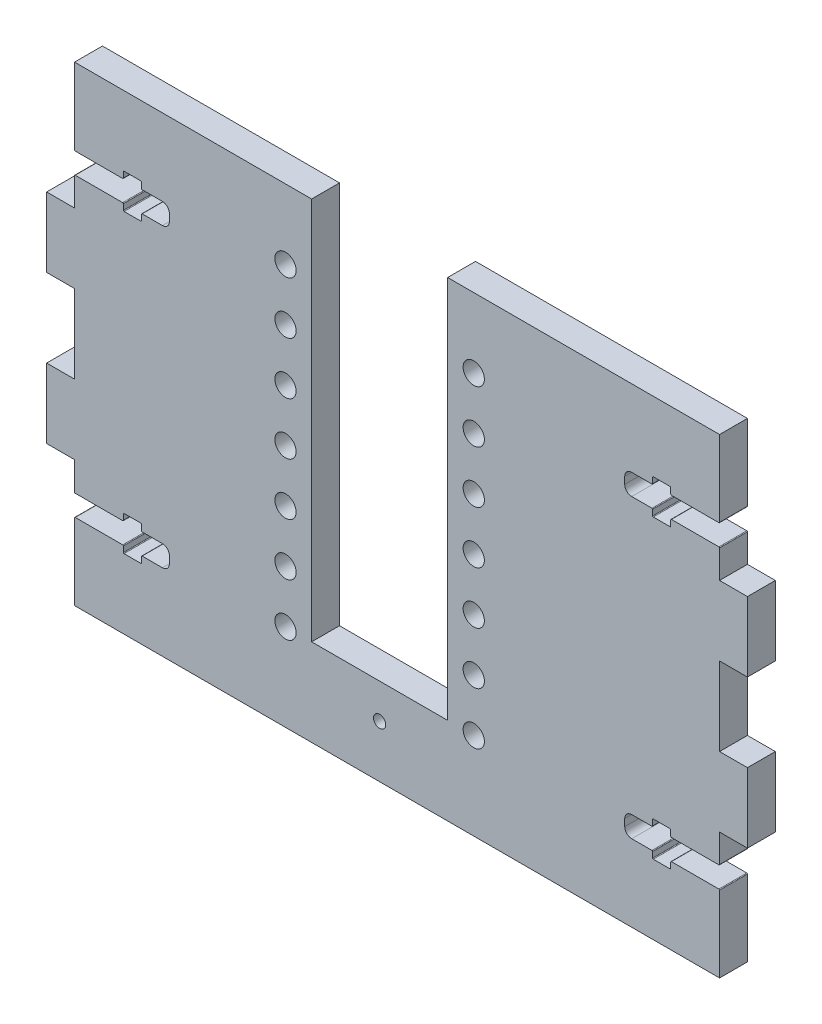
SolidWorks part; units mm, degrees
ref_plane "Front Plane" through (0, 0, 0) normal (0, 0, 1) x (1, 0, 0)
ref_plane "Top Plane" through (0, 0, 0) normal (0, 1, 0) x (1, 0, 0)
ref_plane "Right Plane" through (0, 0, 0) normal (1, 0, 0) x (0, 0, -1)
sketch "Model" plane through (0, 0, 0) normal (0, 0, 1) x (1, 0, 0)
  line L0 (-92.5, 21.8) -> (-92.5, 2)
  line L1 (-78.7, 22) -> (-92.3, 22)
  line L2 (-78.5, 20.2) -> (-78.5, 21.8)
  line L3 (-73.5, 20) -> (-78.3, 20)
  line L4 (-73.3, 21.8) -> (-73.3, 20.2)
  line L5 (-67.3, 22) -> (-73.1, 22)
  line L6 (-65.3, 26) -> (-65.3, 24)
  line L7 (-73.1, 28) -> (-67.3, 28)
  line L8 (-73.3, 29.8) -> (-73.3, 28.2)
  line L9 (-78.3, 30) -> (-73.5, 30)
  line L10 (-78.5, 28.2) -> (-78.5, 29.8)
  line L11 (-92.3, 28) -> (-78.7, 28)
  line L12 (-92.5, 36.25) -> (-92.5, 28.2)
  line L13 (-100.5, 36.25) -> (-92.5, 36.25)
  line L14 (-100.5, 56.25) -> (-100.5, 36.25)
  line L15 (-92.5, 56.25) -> (-100.5, 56.25)
  line L16 (-92.5, 78.75) -> (-92.5, 56.25)
  line L17 (-100.5, 78.75) -> (-92.5, 78.75)
  line L18 (-100.5, 98.75) -> (-100.5, 78.75)
  line L19 (-92.5, 98.75) -> (-100.5, 98.75)
  line L20 (-92.5, 106.8) -> (-92.5, 98.75)
  line L21 (-78.7, 107) -> (-92.3, 107)
  line L22 (-78.5, 105.2) -> (-78.5, 106.8)
  line L23 (-73.5, 105) -> (-78.3, 105)
  line L24 (-73.3, 106.8) -> (-73.3, 105.2)
  line L25 (-67.3, 107) -> (-73.1, 107)
  line L26 (-65.3, 111) -> (-65.3, 109)
  line L27 (-73.1, 113) -> (-67.3, 113)
  line L28 (-73.3, 114.8) -> (-73.3, 113.2)
  line L29 (-78.3, 115) -> (-73.5, 115)
  line L30 (-78.5, 113.2) -> (-78.5, 114.8)
  line L31 (-92.3, 113) -> (-78.7, 113)
  line L32 (-92.5, 133) -> (-92.5, 113.2)
  line L33 (-24.5, 135) -> (-90.5, 135)
  line L34 (-90.5, 135) -> (-92.5, 135)
  line L35 (-92.5, 133) -> (-92.5, 135)
  line L36 (-92.5, 2) -> (-92.5, 0)
  line L37 (90.5, 135) -> (14.5, 135)
  line L38 (92.5, 113.2) -> (92.5, 133)
  line L39 (78.7, 113) -> (92.3, 113)
  line L40 (78.5, 114.8) -> (78.5, 113.2)
  line L41 (73.5, 115) -> (78.3, 115)
  line L42 (73.3, 113.2) -> (73.3, 114.8)
  line L43 (67.3, 113) -> (73.1, 113)
  line L44 (65.3, 109) -> (65.3, 111)
  line L45 (73.1, 107) -> (67.3, 107)
  line L46 (73.3, 105.2) -> (73.3, 106.8)
  line L47 (78.3, 105) -> (73.5, 105)
  line L48 (78.5, 106.8) -> (78.5, 105.2)
  line L49 (92.3, 107) -> (78.7, 107)
  line L50 (92.5, 98.75) -> (92.5, 106.8)
  line L51 (100.5, 98.75) -> (92.5, 98.75)
  line L52 (100.5, 78.75) -> (100.5, 98.75)
  line L53 (92.5, 78.75) -> (100.5, 78.75)
  line L54 (92.5, 56.25) -> (92.5, 78.75)
  line L55 (100.5, 56.25) -> (92.5, 56.25)
  line L56 (100.5, 36.25) -> (100.5, 56.25)
  line L57 (92.5, 36.25) -> (100.5, 36.25)
  line L58 (92.5, 28.2) -> (92.5, 36.25)
  line L59 (78.7, 28) -> (92.3, 28)
  line L60 (78.5, 29.8) -> (78.5, 28.2)
  line L61 (73.5, 30) -> (78.3, 30)
  line L62 (73.3, 28.2) -> (73.3, 29.8)
  line L63 (67.3, 28) -> (73.1, 28)
  line L64 (65.3, 24) -> (65.3, 26)
  line L65 (73.1, 22) -> (67.3, 22)
  line L66 (73.3, 20.2) -> (73.3, 21.8)
  line L67 (78.3, 20) -> (73.5, 20)
  line L68 (78.5, 21.8) -> (78.5, 20.2)
  line L69 (92.3, 22) -> (78.7, 22)
  line L70 (92.5, 2) -> (92.5, 21.8)
  line L71 (-90.5, 0) -> (90.5, 0)
  line L72 (-24.5, 135) -> (-24.5, 25)
  line L73 (-24.5, 25) -> (14.5, 25)
  line L74 (14.5, 25) -> (14.5, 135)
  line L75 (-90.5, 0) -> (-92.5, 0)
  line L76 (90.5, 135) -> (92.5, 135)
  line L77 (92.5, 133) -> (92.5, 135)
  line L78 (92.5, 2) -> (92.5, 0)
  line L79 (90.5, 0) -> (92.5, 0)
  arc A0 (-92.3, 22) -> (-92.5, 21.8) centre (-92.3, 21.8) ccw
  arc A1 (-78.5, 21.8) -> (-78.7, 22) centre (-78.7, 21.8) ccw
  arc A2 (-78.5, 20.2) -> (-78.3, 20) centre (-78.3, 20.2) ccw
  arc A3 (-73.5, 20) -> (-73.3, 20.2) centre (-73.5, 20.2) ccw
  arc A4 (-73.1, 22) -> (-73.3, 21.8) centre (-73.1, 21.8) ccw
  arc A5 (-67.3, 22) -> (-65.3, 24) centre (-67.3, 24) ccw
  arc A6 (-65.3, 26) -> (-67.3, 28) centre (-67.3, 26) ccw
  arc A7 (-73.3, 28.2) -> (-73.1, 28) centre (-73.1, 28.2) ccw
  arc A8 (-73.3, 29.8) -> (-73.5, 30) centre (-73.5, 29.8) ccw
  arc A9 (-78.3, 30) -> (-78.5, 29.8) centre (-78.3, 29.8) ccw
  arc A10 (-78.7, 28) -> (-78.5, 28.2) centre (-78.7, 28.2) ccw
  arc A11 (-92.5, 28.2) -> (-92.3, 28) centre (-92.3, 28.2) ccw
  arc A12 (-92.3, 107) -> (-92.5, 106.8) centre (-92.3, 106.8) ccw
  arc A13 (-78.5, 106.8) -> (-78.7, 107) centre (-78.7, 106.8) ccw
  arc A14 (-78.5, 105.2) -> (-78.3, 105) centre (-78.3, 105.2) ccw
  arc A15 (-73.5, 105) -> (-73.3, 105.2) centre (-73.5, 105.2) ccw
  arc A16 (-73.1, 107) -> (-73.3, 106.8) centre (-73.1, 106.8) ccw
  arc A17 (-67.3, 107) -> (-65.3, 109) centre (-67.3, 109) ccw
  arc A18 (-65.3, 111) -> (-67.3, 113) centre (-67.3, 111) ccw
  arc A19 (-73.3, 113.2) -> (-73.1, 113) centre (-73.1, 113.2) ccw
  arc A20 (-73.3, 114.8) -> (-73.5, 115) centre (-73.5, 114.8) ccw
  arc A21 (-78.3, 115) -> (-78.5, 114.8) centre (-78.3, 114.8) ccw
  arc A22 (-78.7, 113) -> (-78.5, 113.2) centre (-78.7, 113.2) ccw
  arc A23 (-92.5, 113.2) -> (-92.3, 113) centre (-92.3, 113.2) ccw
  circle A24 centre (-32, 55) radius 3.05
  circle A25 centre (-32, 70) radius 3.05
  circle A26 centre (22, 100) radius 3.05
  circle A27 centre (22, 85) radius 3.05
  circle A28 centre (22, 25) radius 3.05
  circle A29 centre (22, 40) radius 3.05
  arc A30 (92.3, 113) -> (92.5, 113.2) centre (92.3, 113.2) ccw
  arc A31 (78.5, 113.2) -> (78.7, 113) centre (78.7, 113.2) ccw
  arc A32 (78.5, 114.8) -> (78.3, 115) centre (78.3, 114.8) ccw
  arc A33 (73.5, 115) -> (73.3, 114.8) centre (73.5, 114.8) ccw
  arc A34 (73.1, 113) -> (73.3, 113.2) centre (73.1, 113.2) ccw
  arc A35 (67.3, 113) -> (65.3, 111) centre (67.3, 111) ccw
  arc A36 (65.3, 109) -> (67.3, 107) centre (67.3, 109) ccw
  arc A37 (73.3, 106.8) -> (73.1, 107) centre (73.1, 106.8) ccw
  arc A38 (73.3, 105.2) -> (73.5, 105) centre (73.5, 105.2) ccw
  arc A39 (78.3, 105) -> (78.5, 105.2) centre (78.3, 105.2) ccw
  arc A40 (78.7, 107) -> (78.5, 106.8) centre (78.7, 106.8) ccw
  arc A41 (92.5, 106.8) -> (92.3, 107) centre (92.3, 106.8) ccw
  arc A42 (92.3, 28) -> (92.5, 28.2) centre (92.3, 28.2) ccw
  arc A43 (78.5, 28.2) -> (78.7, 28) centre (78.7, 28.2) ccw
  arc A44 (78.5, 29.8) -> (78.3, 30) centre (78.3, 29.8) ccw
  arc A45 (73.5, 30) -> (73.3, 29.8) centre (73.5, 29.8) ccw
  arc A46 (73.1, 28) -> (73.3, 28.2) centre (73.1, 28.2) ccw
  arc A47 (67.3, 28) -> (65.3, 26) centre (67.3, 26) ccw
  arc A48 (65.3, 24) -> (67.3, 22) centre (67.3, 24) ccw
  arc A49 (73.3, 21.8) -> (73.1, 22) centre (73.1, 21.8) ccw
  arc A50 (73.3, 20.2) -> (73.5, 20) centre (73.5, 20.2) ccw
  arc A51 (78.3, 20) -> (78.5, 20.2) centre (78.3, 20.2) ccw
  arc A52 (78.7, 22) -> (78.5, 21.8) centre (78.7, 21.8) ccw
  arc A53 (92.5, 21.8) -> (92.3, 22) centre (92.3, 21.8) ccw
  circle A54 centre (-32, 40) radius 3.05
  circle A55 centre (-32, 25) radius 3.05
  circle A56 centre (22, 70) radius 3.05
  circle A57 centre (22, 55) radius 3.05
  circle A58 centre (22, 115) radius 3.05
  circle A59 centre (-32, 115) radius 3.05
  circle A60 centre (-32, 85) radius 3.05
  circle A61 centre (-32, 100) radius 3.05
  circle A62 centre (-5, 15) radius 1.75
extrude "Boss-Extrude2" add sketch "Model" along normal blind 8
